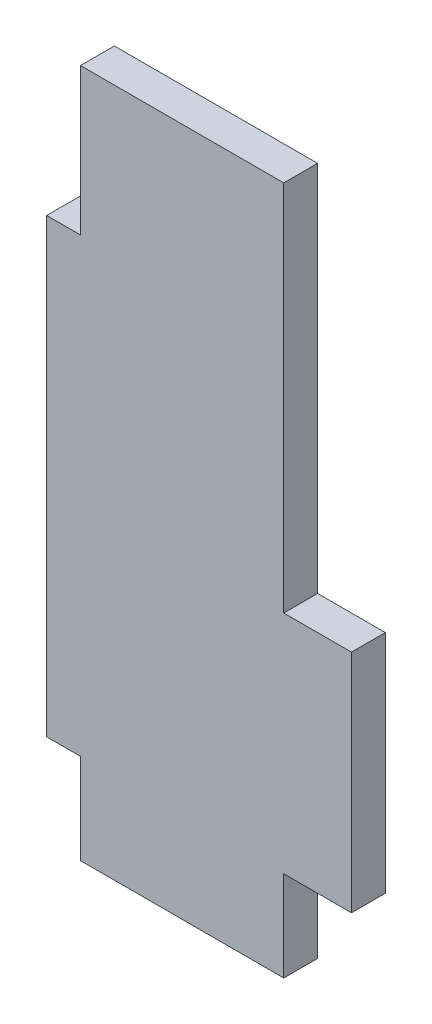
SolidWorks part; units mm, degrees
ref_plane "Front Plane" through (0, 0, 0) normal (0, 0, 1) x (1, 0, 0)
ref_plane "Top Plane" through (0, 0, 0) normal (0, 1, 0) x (1, 0, 0)
ref_plane "Right Plane" through (0, 0, 0) normal (1, 0, 0) x (0, 0, -1)
sketch "Sketch1" plane through (0, 0, 0) normal (0, 0, 1) x (1, 0, 0)
  line L1 (-18, 61) -> (0, 61)
  line L2 (-18, 61) -> (-18, 0)
  line L3 (-18, 0) -> (0, 0)
  line L4 (0, 61) -> (0, 0)
  dimension "D1" = 61
  dimension "D2" = 18
extrude "Base Shape" add sketch "Sketch1" along normal blind 3
sketch "Sketch2" plane through (0, 0, 3) normal (0, 0, 1) x (1, 0, 0)
  line L0 (-18, 61) -> (-18, 0) construction
  line L1 (-18, 8) -> (-21, 8)
  line L2 (-18, 8) -> (-18, 48)
  line L3 (-18, 48) -> (-21, 48)
  line L4 (-21, 8) -> (-21, 48)
  line L5 (0, 0) -> (0, 61) construction
  line L6 (0, 8) -> (6, 8)
  line L7 (0, 8) -> (0, 28)
  line L8 (0, 28) -> (6, 28)
  line L9 (6, 8) -> (6, 28)
  line L10 (-18, 0) -> (0, 0) construction
  line M11 (0, 0) -> (0, 61)
  dimension "D1" = 8
  dimension "D2" = 40
  dimension "D3" = 3
  dimension "D4" = 6
  dimension "D5" = 20
extrude "Boss-Extrude2" add sketch "Sketch2" against normal up to surface (3 mm away) contours L6 L9 L8 M11 | L4 L3 L2 L1 up to face at (-9, 30.5, 0)
